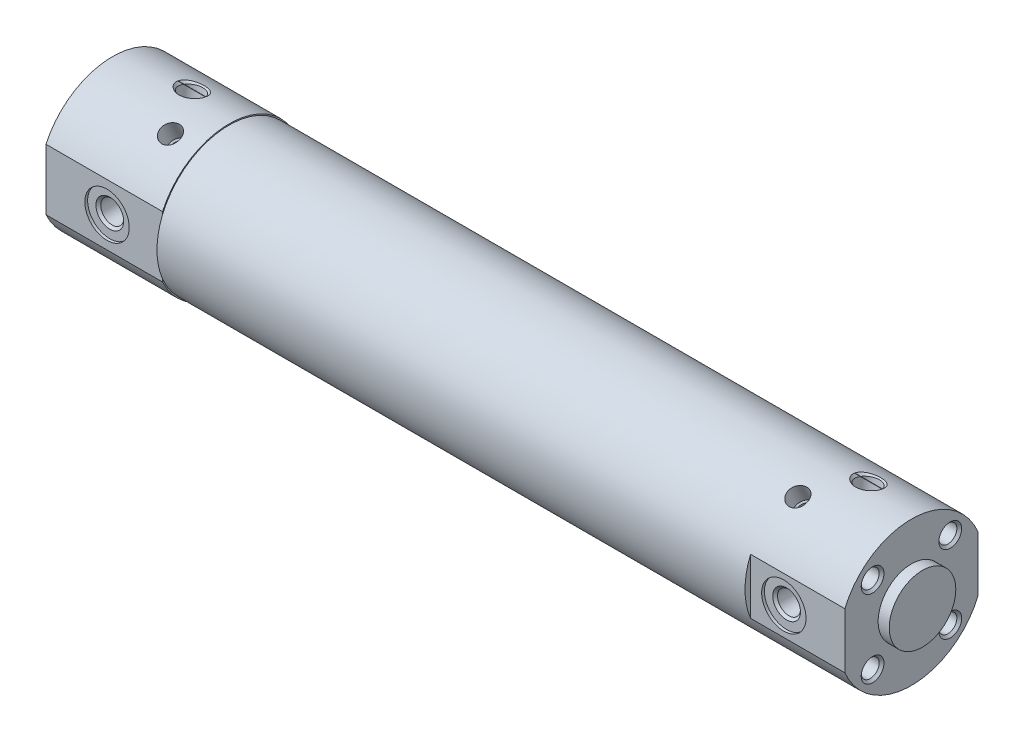
SolidWorks part; units mm, degrees
ref_plane "正面" through (0, 0, 0) normal (0, 0, 1) x (1, 0, 0)
ref_plane "平面" through (0, 0, 0) normal (0, 1, 0) x (1, 0, 0)
ref_plane "右側面" through (0, 0, 0) normal (1, 0, 0) x (0, 0, -1)
ref_plane "平面4" through (0, 0, 0) normal (-1, 0, 0) x (0, -1, 0)
sketch "ｽｹｯﾁ1" plane through (0, 0, 0) normal (-1, 0, 0) x (0, -1, 0)
  line L0 (-5.4991, -12) -> (5.4991, -12)
  line L1 (5.4991, 12) -> (-5.4991, 12)
  arc A0 (-5.4991, 12) -> (-5.4991, -12) centre (0, 0) ccw
  arc A1 (5.4991, -12) -> (5.4991, 12) centre (0, 0) ccw
extrude "ﾎﾞｽ - 押し出し1" add sketch "ｽｹｯﾁ1" against normal blind 21
ref_plane "平面5" through (21, 0, 0) normal (-1, 0, 0) x (0, -1, 0)
sketch "ｽｹｯﾁ2" plane through (21, 0, 0) normal (-1, 0, 0) x (0, -1, 0)
  circle A0 centre (0, 0) radius 13
extrude "ﾎﾞｽ - 押し出し2" add sketch "ｽｹｯﾁ2" against normal blind 123
sketch "ｽｹｯﾁ3" plane through (144, 0, 0) normal (1, 0, 0) x (0, 0, -1)
  line L0 (-12, -5) -> (-12, 5)
  arc A0 (-12, 5) -> (-12, -5) centre (0, 0) ccw
extrude "ｶｯﾄ - 押し出し1" cut sketch "ｽｹｯﾁ3" against normal blind 17
sketch "ｽｹｯﾁ4" plane through (144, 0, 0) normal (1, 0, 0) x (0, 0, -1)
  line L0 (12, 5) -> (12, -5)
  arc A0 (12, -5) -> (12, 5) centre (0, 0) ccw
extrude "ｶｯﾄ - 押し出し2" cut sketch "ｽｹｯﾁ4" against normal blind 17
sketch "ｽｹｯﾁ5" plane through (144, 0, 0) normal (1, 0, 0) x (0, 0, -1)
  circle A0 centre (0, 0) radius 6
extrude "ﾎﾞｽ - 押し出し3" add sketch "ｽｹｯﾁ5" along normal blind 2
sketch "ｽｹｯﾁ6" plane through (0, 0, 0) normal (0, 0, 1) x (1, 0, 0)
  line L0 (-2, 6) -> (-2, 0)
  line L1 (-2, 0) -> (0, 0)
  line L2 (0, 0) -> (0, 6)
  line L3 (0, 6) -> (-2, 6)
  line L4 (-2, 0) -> (0, 0) construction
revolve "回転1" add sketch "ｽｹｯﾁ6" angle 360 about L4
sketch "ｽｹｯﾁ7" plane through (0, 0, 0) normal (0, 0, 1) x (1, 0, 0)
  line L0 (-2, 4) -> (-2, 0)
  line L1 (-2, 0) -> (99, 0)
  line L2 (99, 0) -> (99, 10)
  line L3 (99, 10) -> (19, 10)
  line L4 (19, 10) -> (19, 4)
  line L5 (19, 4) -> (-2, 4)
  line L6 (-2, 0) -> (99, 0) construction
revolve "ｶｯﾄ - 回転1" cut sketch "ｽｹｯﾁ7" angle 360 about L6
ref_plane "平面6" through (16, 0, 0) normal (1, 0, 0) x (0, 0, -1)
sketch "ｽｹｯﾁ8" plane through (16, 0, 0) normal (1, 0, 0) x (0, 0, -1)
  line L0 (-3.9925, 12.7028) -> (-5.5786, 11.9633)
  line L1 (-5.5786, 11.9633) -> (-1.6772, 3.5968)
  line L2 (-1.6772, 3.5968) -> (-1.2241, 3.8081)
  line L3 (-1.2241, 3.8081) -> (-2.5812, 6.7186)
  line L4 (-2.5812, 6.7186) -> (-1.6749, 7.1412)
  line L5 (-1.6749, 7.1412) -> (-2.6258, 9.1804)
  line L6 (-2.6258, 9.1804) -> (-2.5049, 9.5126)
  line L7 (-2.5049, 9.5126) -> (-3.9925, 12.7028)
  line L8 (-5.5786, 11.9633) -> (-1.6772, 3.5968) construction
revolve "ｶｯﾄ - 回転2" cut sketch "ｽｹｯﾁ8" angle 360 about L8
ref_plane "平面7" through (129, 0, 0) normal (1, 0, 0) x (0, 0, -1)
sketch "ｽｹｯﾁ9" plane through (129, 0, 0) normal (1, 0, 0) x (0, 0, -1)
  line L0 (-3.908, 12.5216) -> (-5.494, 11.782)
  line L1 (-5.494, 11.782) -> (-0.9213, 1.9758)
  line L2 (-0.9213, 1.9758) -> (-0.4682, 2.1871)
  line L3 (-0.4682, 2.1871) -> (-2.5812, 6.7186)
  line L4 (-2.5812, 6.7186) -> (-1.6749, 7.1412)
  line L5 (-1.6749, 7.1412) -> (-2.6258, 9.1804)
  line L6 (-2.6258, 9.1804) -> (-2.5049, 9.5126)
  line L7 (-2.5049, 9.5126) -> (-3.908, 12.5216)
  line L8 (-5.494, 11.782) -> (-0.9213, 1.9758) construction
revolve "ｶｯﾄ - 回転3" cut sketch "ｽｹｯﾁ9" angle 360 about L8
hole_wizard "M3 すきま穴1" positions "ｽｹｯﾁ11" profile "ｽｹｯﾁ10" hole size "M3" standard "Ansi Metric"
sketch "ｽｹｯﾁ11" plane through (144, 0, 0) normal (1, 0, 0) x (0, 0, -1)
  point P0 (-7, 7)
  point P1 (-7, -7)
  point P2 (7, -7)
  point P3 (7, 7)
sketch "ｽｹｯﾁ10" plane through (144, 7, 7) normal (0, 1, 0) x (0, 0, -1)
  line L0 (0, 0) -> (0, 7.9359)
  line L1 (0, 7.9359) -> (1.621, 7)
  line L2 (1.621, 7) -> (1.621, 0)
  line L5 (1.621, 0) -> (0, 0)
  line L10 (0, 7.9359) -> (-1.621, 7) construction
  line L11 (0, -6.35) -> (0, 107.95) construction
  dimension "穴の直径" = 3.242
  dimension "穴の深さ" = 7
  dimension "ﾄﾞﾘﾙ角度" = 120
hole_wizard "M3.5 六角小ねじ用座ぐり穴1" positions "ｽｹｯﾁ13" profile "ｽｹｯﾁ12" counterbore size "M3.5" standard "Ansi Metric"
sketch "ｽｹｯﾁ13" plane through (0, 0, 12) normal (0, 0, 1) x (1, 0, 0)
  point P0 (11, 0)
  point P1 (133, 0)
sketch "ｽｹｯﾁ12" plane through (11, 0, 12) normal (1, 0, 0) x (0, -1, 0)
  line L0 (0, 0) -> (0, 6)
  line L1 (0, 6) -> (2.067, 6)
  line L2 (2.067, 6) -> (2.067, 0.5)
  line L3 (2.067, 0.5) -> (4, 0.5)
  line L4 (4, 0.5) -> (4, 0)
  line L5 (4, 0) -> (0, 0)
  line L10 (0, 6) -> (-2.067, 6) construction
  line L11 (0, -6.35) -> (0, 107.95) construction
  dimension "穴の直径" = 4.134
  dimension "穴の深さ" = 6
  dimension "座ぐり穴の直径" = 8
  dimension "座ぐり穴の深さ" = 0.5
  dimension "ﾄﾞﾘﾙ角度" = 180
ref_plane "平面8" through (0, 12.9994, -2.2921) normal (0, 0.9848, -0.1736) x (1, 0, 0)
hole_wizard "M3.5 皿頭小ねじ(100)用皿穴1" positions "ｽｹｯﾁ15" profile "ｽｹｯﾁ14" countersink size "M3.5" standard "Ansi Metric"
sketch "ｽｹｯﾁ15" plane through (0, 12.9994, -2.2921) normal (0, 0.9848, -0.1736) x (1, 0, 0)
  point P0 (12, 0)
sketch "ｽｹｯﾁ14" plane through (12, 12.9994, -2.2921) normal (1, 0, 0) x (0, 0.1736, 0.9848)
  line L0 (0, 0) -> (0, 6.1933)
  line L1 (0, 6.1933) -> (2.067, 4.9999)
  line L2 (2.067, 4.9999) -> (2.067, 0.4329)
  line L3 (2.067, 0.4329) -> (2.4999, 0)
  line L5 (2.4999, 0) -> (0, 0)
  line L6 (-2.067, 0.4329) -> (-2.4999, 0) construction
  line L10 (0, 6.1933) -> (-2.067, 4.9999) construction
  line L11 (0, -6.35) -> (0, 107.95) construction
  dimension "穴の直径" = 4.134
  dimension "穴の深さ" = 4.9999
  dimension "表面の皿穴の直径" = 4.9999
  dimension "表面の皿穴の角度" = 90
  dimension "ﾄﾞﾘﾙ角度" = 120
hole_wizard "M3.5 六角小ねじ用座ぐり穴2" positions "ｽｹｯﾁ17" profile "ｽｹｯﾁ16" counterbore size "M3.5" standard "Ansi Metric"
sketch "ｽｹｯﾁ17" plane through (0, 0, -12) normal (0, 0, -1) x (-1, 0, 0)
  point P0 (-11, 0)
  point P1 (-133, 0)
sketch "ｽｹｯﾁ16" plane through (11, 0, -12) normal (1, 0, 0) x (0, 1, 0)
  line L0 (0, 0) -> (0, 6)
  line L1 (0, 6) -> (2.067, 6)
  line L2 (2.067, 6) -> (2.067, 0.5)
  line L3 (2.067, 0.5) -> (4, 0.5)
  line L4 (4, 0.5) -> (4, 0)
  line L5 (4, 0) -> (0, 0)
  line L10 (0, 6) -> (-2.067, 6) construction
  line L11 (0, -6.35) -> (0, 107.95) construction
  dimension "穴の直径" = 4.134
  dimension "穴の深さ" = 6
  dimension "座ぐり穴の直径" = 8
  dimension "座ぐり穴の深さ" = 0.5
  dimension "ﾄﾞﾘﾙ角度" = 180
hole_wizard "M3 すきま穴2" positions "ｽｹｯﾁ19" profile "ｽｹｯﾁ18" hole size "M3" standard "Ansi Metric"
sketch "ｽｹｯﾁ19" plane through (0, 0, 0) normal (-1, 0, 0) x (0, 0, 1)
  point P0 (7, 7)
  point P1 (7, -7)
  point P2 (-7, -7)
  point P3 (-7, 7)
sketch "ｽｹｯﾁ18" plane through (0, 7, 7) normal (0, 1, 0) x (0, 0, 1)
  line L0 (0, 0) -> (0, 7.9359)
  line L1 (0, 7.9359) -> (1.621, 7)
  line L2 (1.621, 7) -> (1.621, 0)
  line L5 (1.621, 0) -> (0, 0)
  line L10 (0, 7.9359) -> (-1.621, 7) construction
  line L11 (0, -6.35) -> (0, 107.95) construction
  dimension "穴の直径" = 3.242
  dimension "穴の深さ" = 7
  dimension "ﾄﾞﾘﾙ角度" = 120
ref_plane "平面9" through (0, 12.8024, -2.2574) normal (0, 0.9848, -0.1736) x (1, 0, 0)
hole_wizard "M3.5 皿頭小ねじ(100)用皿穴2" positions "ｽｹｯﾁ21" profile "ｽｹｯﾁ20" countersink size "M3.5" standard "Ansi Metric"
sketch "ｽｹｯﾁ21" plane through (0, 12.8024, -2.2574) normal (0, 0.9848, -0.1736) x (1, 0, 0)
  point P0 (134, 0)
sketch "ｽｹｯﾁ20" plane through (134, 12.8024, -2.2574) normal (1, 0, 0) x (0, 0.1736, 0.9848)
  line L0 (0, 0) -> (0, 6.1933)
  line L1 (0, 6.1933) -> (2.067, 4.9999)
  line L2 (2.067, 4.9999) -> (2.067, 0.4329)
  line L3 (2.067, 0.4329) -> (2.4999, 0)
  line L5 (2.4999, 0) -> (0, 0)
  line L6 (-2.067, 0.4329) -> (-2.4999, 0) construction
  line L10 (0, 6.1933) -> (-2.067, 4.9999) construction
  line L11 (0, -6.35) -> (0, 107.95) construction
  dimension "穴の直径" = 4.134
  dimension "穴の深さ" = 4.9999
  dimension "表面の皿穴の直径" = 4.9999
  dimension "表面の皿穴の角度" = 90
  dimension "ﾄﾞﾘﾙ角度" = 120
chamfer "面取り1" distance 0.433 angle 45 12 edges at (13.067, 0, 11.5) (144, 7, -8.621) (144, -7, 5.379) (0, 7, 8.621) (135.067, 0, 11.5) (0, -7, 8.621) (144, 7, 5.379) (0, -7, -5.379) (144, -7, -8.621) (0, 7, -5.379) (133, 2.067, -11.5) (11, 2.067, -11.5)
